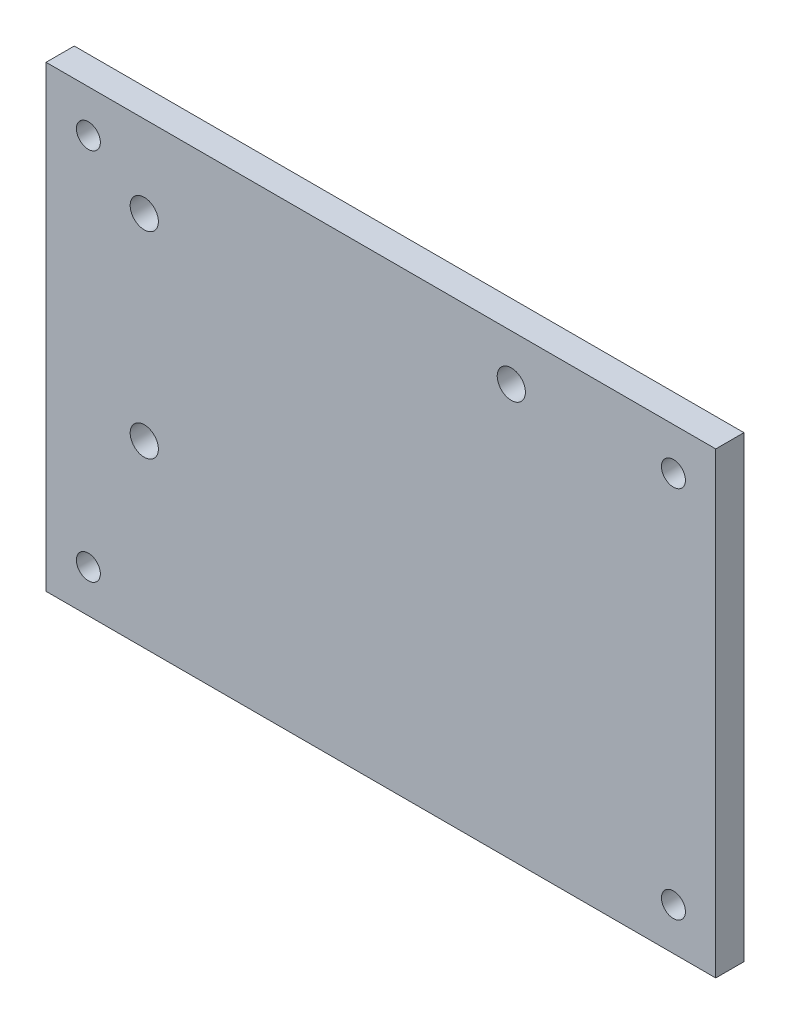
SolidWorks part; units mm, degrees
ref_plane "Plan de face" through (0, 0, 0) normal (0, 0, 1) x (1, 0, 0)
ref_plane "Plan de dessus" through (0, 0, 0) normal (0, 1, 0) x (1, 0, 0)
ref_plane "Plan de droite" through (0, 0, 0) normal (1, 0, 0) x (0, 0, -1)
sketch "Esquisse1" plane through (0, 0, 0) normal (0, 0, 1) x (1, 0, 0)
  line L0 (0, 32.5) -> (0, -32.5) construction
  line L1 (-47.5, 32.5) -> (47.5, 32.5)
  line L2 (-47.5, 32.5) -> (-47.5, -32.5)
  line L3 (-47.5, -32.5) -> (47.5, -32.5)
  line L4 (47.5, 32.5) -> (47.5, -32.5)
  line L5 (-47.5, 0) -> (47.5, 0) construction
  point P6 (0, 0)
  dimension "D1" = 65
  dimension "D2" = 95
extrude "Boss.-Extru.1" add sketch "Esquisse1" along normal blind 4
sketch "Esquisse2" plane through (0, 0, 0) normal (0, 0, -1) x (-1, 0, 0)
  line L0 (-47.5, -32.5) -> (-47.5, 32.5) construction
  line L1 (-47.5, 32.5) -> (47.5, 32.5) construction
  line L3 (0, 55) -> (0, -55) construction
  line L5 (55, 0) -> (-55, 0) construction
  circle A0 centre (-41.5, 26.5) radius 1.7
  circle A1 centre (41.5, 26.5) radius 1.7
  circle A2 centre (-41.5, -26.5) radius 1.7
  circle A3 centre (41.5, -26.5) radius 1.7
  dimension "D1" = 3.4
  dimension "D2" = 6
  dimension "D3" = 6
extrude "Enlèv. mat.-Extru.1" cut sketch "Esquisse2" against normal blind 5
sketch "Esquisse3" plane through (0, 0, 4) normal (0, 0, 1) x (1, 0, 0)
  line L0 (47.5, -32.5) -> (47.5, 32.5) construction
  line L1 (47.5, 32.5) -> (-47.5, 32.5) construction
  circle A0 centre (18.5, 25.96) radius 2
  circle A1 centre (-33.57, 20.88) radius 2
  circle A2 centre (-33.57, -7.06) radius 2
  point P6 (-37.0946, -19.6735)
  point P11 (-38.57, -13.06)
  point P12 (-28.57, -13.06)
  point P13 (0, 0)
  dimension "D1" = 4
  dimension "D2" = 52.07
  dimension "D3" = 27.94
  dimension "D4" = 29
  dimension "D5" = 6.54
  dimension "D6" = 5.08
extrude "Enlèv. mat.-Extru.2" cut sketch "Esquisse3" against normal blind 3
